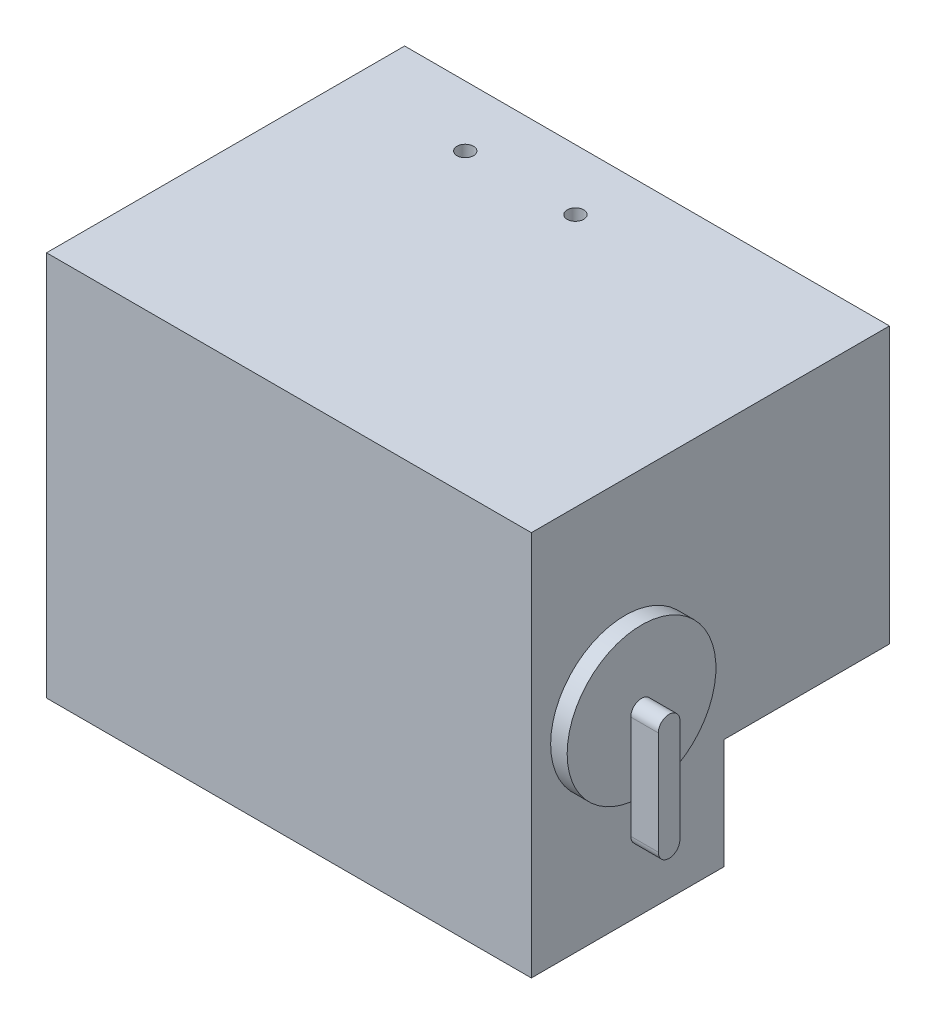
SolidWorks part; units mm, degrees
ref_plane "前视基准面" through (0, 0, 0) normal (0, 0, 1) x (1, 0, 0)
ref_plane "上视基准面" through (0, 0, 0) normal (0, 1, 0) x (1, 0, 0)
ref_plane "右视基准面" through (0, 0, 0) normal (1, 0, 0) x (0, 0, -1)
other "Configuration Table"
sketch "草图1" plane through (0, 0, 0) normal (0, 0, 1) x (1, 0, 0)
  line L1 (-44, 35) -> (44, 35)
  line L2 (-44, 35) -> (-44, -35)
  line L3 (-44, -35) -> (44, -35)
  line L4 (44, 35) -> (44, -35)
  line L5 (-44, 35) -> (44, -35) construction
  line L6 (-44, -35) -> (44, 35) construction
  point P0 (0, 0)
  dimension "D1" = 88
  dimension "D2" = 70
extrude "凸台-拉伸1" add sketch "草图1" along normal blind 35
sketch "草图3" plane through (0, 0, 0) normal (0, 0, -1) x (-1, 0, 0)
  line L0 (44, 35) -> (44, -35) construction
  line L1 (-44, 35) -> (44, 35)
  line L2 (-44, 35) -> (-44, -15)
  line L3 (-44, -15) -> (44, -15)
  line L4 (44, 35) -> (44, -15)
  dimension "D1" = 50
extrude "凸台-拉伸2" add sketch "草图3" along normal blind 30
sketch "草图6" plane through (44, 0, 0) normal (1, 0, 0) x (0, 0, -1)
  line L0 (-35, -35) -> (0, -35) construction
  line L1 (-35, -35) -> (-35, 35) construction
  circle A0 centre (-18, 0) radius 13.5
  dimension "D1" = 27
  dimension "D2" = 35
  dimension "D3" = 17
extrude "凸台-拉伸3" add sketch "草图6" along normal blind 3
sketch "草图7" plane through (47, 0, 0) normal (1, 0, 0) x (0, 0, -1)
  line L0 (-18, 0) -> (-18, -18.7406) construction
  line L1 (-16.0428, 0) -> (-16.0428, -18.7406)
  line L2 (-19.9572, 0) -> (-19.9572, -18.7406)
  circle A0 centre (-18, 0) radius 13.5 construction
  circle A1 centre (-18, 0) radius 13.5
  arc A2 (-16.0428, 0) -> (-19.9572, 0) centre (-18, 0) ccw
  arc A3 (-19.9572, -18.7406) -> (-16.0428, -18.7406) centre (-18, -18.7406) ccw
  point P3 (-18, -9.3703)
extrude "凸台-拉伸4" add sketch "草图7" along normal blind 5 contours L1 A3 L2 A2
sketch "草图8" plane through (0, 35, 0) normal (0, 1, 0) x (1, 0, 0)
  line L0 (-44, 30) -> (44, 30) construction
  line L1 (-44, -35) -> (-44, 30) construction
  circle A0 centre (-22, 19) radius 1.5
  circle A1 centre (-2, 19) radius 1.5
  dimension "D1" = 11
  dimension "D2" = 22
  dimension "D3" = 3
  dimension "D4" = 20
extrude "切除-拉伸1" cut sketch "草图8" against normal up to next
